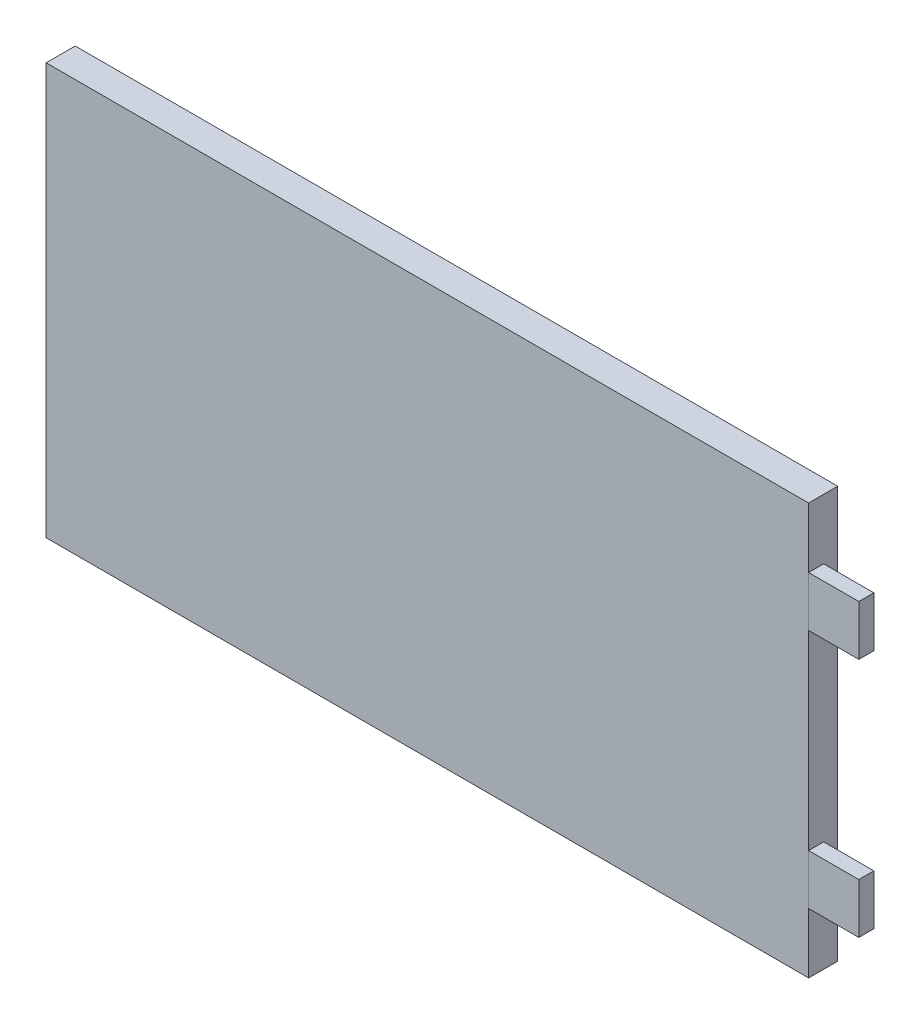
SolidWorks part; units mm, degrees
ref_plane "前视基准面" through (0, 0, 0) normal (0, 0, 1) x (1, 0, 0)
ref_plane "上视基准面" through (0, 0, 0) normal (0, 1, 0) x (1, 0, 0)
ref_plane "右视基准面" through (0, 0, 0) normal (1, 0, 0) x (0, 0, -1)
sketch "草图1" plane through (0, 0, 0) normal (0, 0, 1) x (1, 0, 0)
  line L1 (-38, 20.5) -> (38, 20.5)
  line L2 (-38, 20.5) -> (-38, -20.5)
  line L3 (-38, -20.5) -> (38, -20.5)
  line L4 (38, 20.5) -> (38, -20.5)
  line L5 (-38, 20.5) -> (38, -20.5) construction
  line L6 (-38, -20.5) -> (38, 20.5) construction
  point P0 (0, 0)
  dimension "D1" = 41
  dimension "D2" = 76
extrude "凸台-拉伸1" add sketch "草图1" along normal blind 2.9
sketch "草图2" plane through (0, 0, 2.9) normal (0, 0, 1) x (1, 0, 0)
  line L0 (38, -20.5) -> (38, 20.5) construction
  line L1 (38, 14.5) -> (43, 14.5)
  line L2 (38, 14.5) -> (38, 9.5)
  line L3 (38, 9.5) -> (43, 9.5)
  line L4 (43, 14.5) -> (43, 9.5)
  line L5 (0, 0) -> (24.7358, 0) construction
  line L6 (38, -9.5) -> (43, -9.5)
  line L7 (38, -9.5) -> (38, -14.5)
  line L8 (38, -14.5) -> (43, -14.5)
  line L9 (43, -9.5) -> (43, -14.5)
  line L10 (38, 20.5) -> (-38, 20.5) construction
  dimension "D1" = 5
  dimension "D2" = 5
  dimension "D3" = 6
extrude "凸台-拉伸2" add sketch "草图2" against normal blind 1.5 separate body
